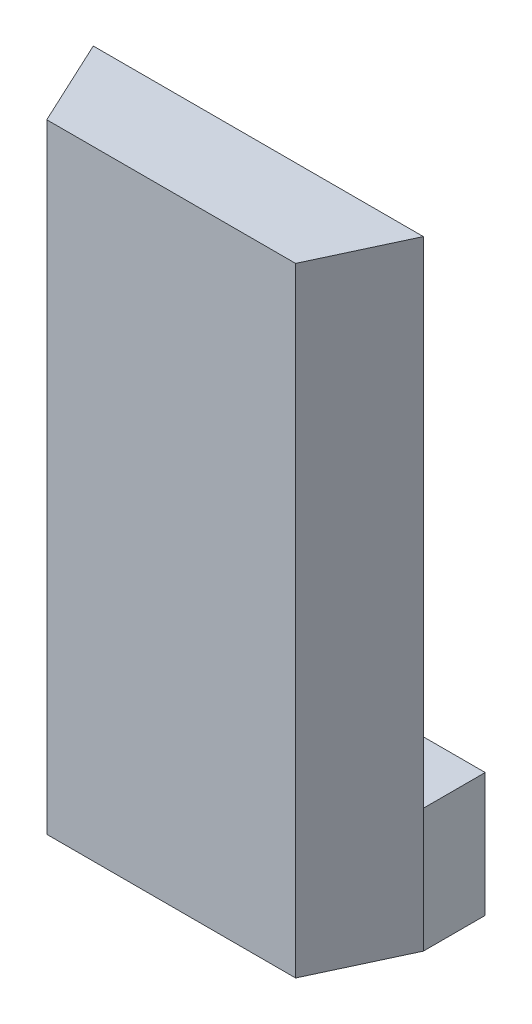
SolidWorks part; units mm, degrees
ref_plane "Alzado" through (0, 0, 0) normal (0, 0, 1) x (1, 0, 0)
ref_plane "Planta" through (0, 0, 0) normal (0, 1, 0) x (1, 0, 0)
ref_plane "Vista lateral" through (0, 0, 0) normal (1, 0, 0) x (0, 0, -1)
sketch "Croquis1" plane through (0, 0, 0) normal (0, 1, 0) x (1, 0, 0)
  line L0 (0, 0) -> (-8, 0)
  line L1 (-8, 0) -> (-8, -1.5)
  line L2 (-8, -1.5) -> (0, -1.5)
  line L3 (0, -1.5) -> (0, 0)
  line L5 (-8, -1.5) -> (-7.0154, -3.6115)
  line L6 (-7.0154, -3.6115) -> (-0.9846, -3.6115)
  line L7 (-0.9846, -3.6115) -> (0, -1.5)
  dimension "D1" = 115
  dimension "D2" = 115
extrude "Saliente-Extruir4" add sketch "Croquis1" along normal blind 15 contours L2 L3 L0 L1 | L6 L7 L2 L5
sketch "Croquis3" plane through (0, 15, 0) normal (0, 1, 0) x (1, 0, 0)
  line L0 (-8, 0) -> (-8, -1.5)
  line L1 (-8, -1.5) -> (0, -1.5)
  line L2 (0, -1.5) -> (0, 0) construction
  line L3 (0, -1.5) -> (0, 0)
  line L4 (0, 0) -> (-8, 0)
sketch "Croquis5" plane through (0, 15, 0) normal (0, 1, 0) x (1, 0, 0)
  line L1 (-8, 0) -> (0, 0)
  line L2 (-8, 0) -> (-8, -1.5)
  line L3 (-8, -1.5) -> (0, -1.5)
  line L4 (0, 0) -> (0, -1.5)
extrude "Cortar-Extruir3" cut sketch "Croquis5" against normal blind 12
ref_plane "Plano4" through (0, 3, 0) normal (-1, 0, 0) x (0, 0, 1)
